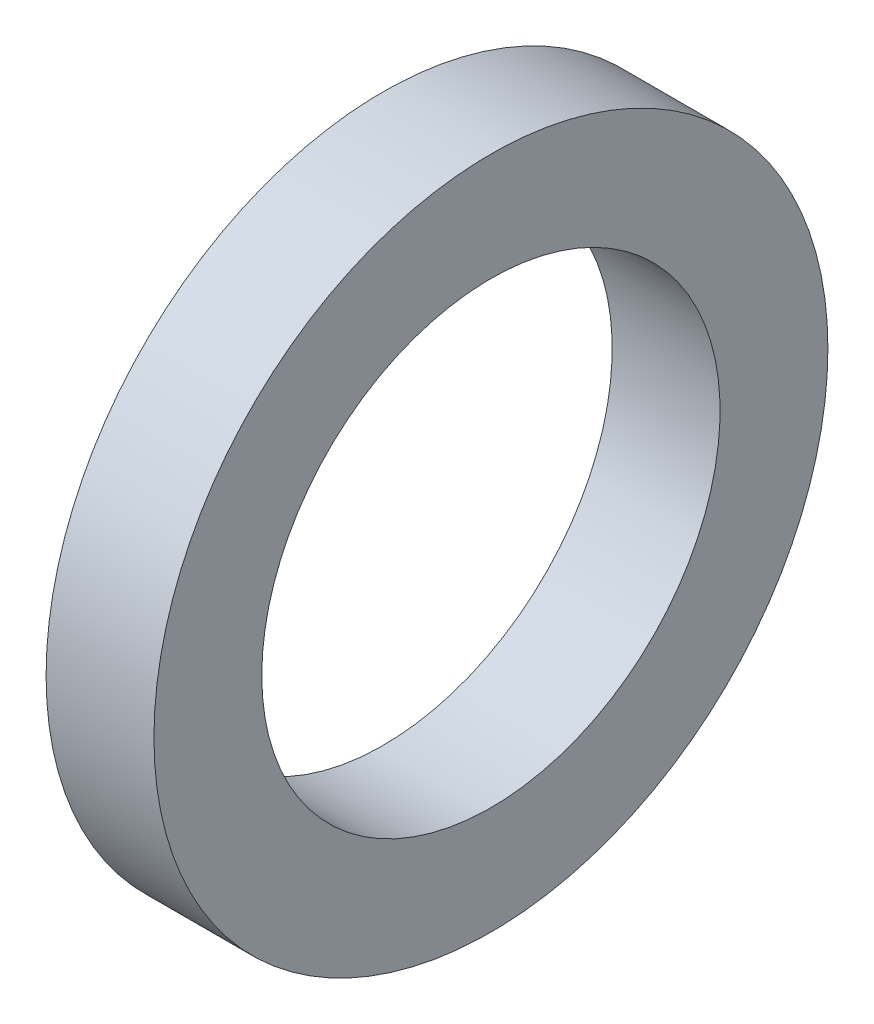
SolidWorks part; units mm, degrees
ref_plane "Front Plane" through (0, 0, 0) normal (0, 0, 1) x (1, 0, 0)
ref_plane "Top Plane" through (0, 0, 0) normal (0, 1, 0) x (1, 0, 0)
ref_plane "Right Plane" through (0, 0, 0) normal (1, 0, 0) x (0, 0, -1)
sketch "Sketch1" plane through (0, 0, 0) normal (0, 0, 1) x (1, 0, 0)
  line L0 (-3.8871, 0) -> (0, 0) construction
  line L2 (0.5, 2.125) -> (-0.5, 2.125)
  line L3 (0.5, 2.125) -> (0.5, 3.125)
  line L4 (0.5, 3.125) -> (-0.5, 3.125)
  line L5 (-0.5, 2.125) -> (-0.5, 3.125)
  line L6 (0.5, 2.125) -> (-0.5, 3.125) construction
  line L7 (0.5, 3.125) -> (-0.5, 2.125) construction
  circle A0 centre (0, 2.625) radius 0.5 construction
  point P9 (0, 0)
  dimension "D1" = 1
  dimension "D2" = 4.25
revolve "Revolve1" add sketch "Sketch1" angle 360 about L0
